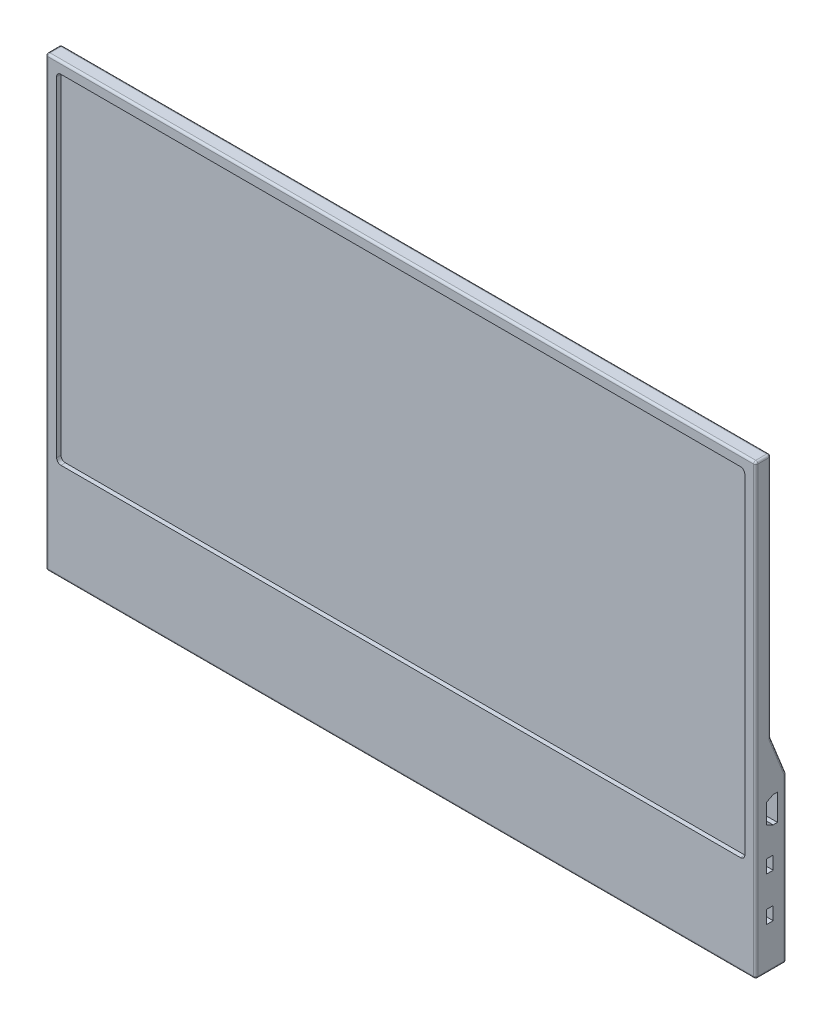
SolidWorks part; units mm, degrees
ref_plane "前视基准面" through (0, 0, 0) normal (0, 0, 1) x (1, 0, 0)
ref_plane "上视基准面" through (0, 0, 0) normal (0, 1, 0) x (1, 0, 0)
ref_plane "右视基准面" through (0, 0, 0) normal (1, 0, 0) x (0, 0, -1)
other "Configuration Table"
ref_plane "基准面1" through (0, 0, 7) normal (0, 0, 1) x (1, 0, 0)
sketch "草图1" plane through (0, 0, 7) normal (0, 0, 1) x (1, 0, 0)
  line L0 (162.5, -102.5) -> (162.5, 102.5)
  line L1 (162.5, 102.5) -> (-162.5, 102.5)
  line L2 (-162.5, 102.5) -> (-162.5, -102.5)
  line L3 (-162.5, -102.5) -> (162.5, -102.5)
  dimension "D1" = 325
  dimension "D2" = 205
extrude "凸台-拉伸1" add sketch "草图1" against normal blind 14
sketch "草图2" plane through (162.5, 0, 0) normal (1, 0, 0) x (0, 0, -1)
  line L0 (7, 102.5) -> (0, 102.5)
  line L1 (0, 102.5) -> (0, -27.5)
  line L2 (0, -27.5) -> (7, -27.5)
  line L3 (7, -27.5) -> (7, 102.5)
  line L4 (-7, -102.5) -> (-7, 102.5) construction
  line L5 (7, -102.5) -> (-7, -102.5) construction
  dimension "D1" = 7
  dimension "D2" = 14
  dimension "D3" = 75
  dimension "D4" = 205
extrude "切除-拉伸1" cut sketch "草图2" against normal through all
sketch "草图3" plane through (162.5, 0, 0) normal (1, 0, 0) x (0, 0, -1)
  line L0 (-2, -43.5) -> (0.9464, -45)
  line L1 (0.9464, -45) -> (2.9464, -45)
  line L2 (2.9464, -45) -> (2.9464, -33)
  line L3 (2.9464, -33) -> (0.9464, -33)
  line L4 (0.9464, -33) -> (-2, -34.5)
  line L5 (-2, -34.5) -> (-2, -43.5)
  line L6 (0, -27.5) -> (7, -27.5) construction
  line L7 (0, 102.5) -> (0, -27.5) construction
  dimension "D1" = 0.9464
  dimension "D2" = 2.9464
  dimension "D3" = 2
  dimension "D4" = 5.5
  dimension "D5" = 7
  dimension "D6" = 16
  dimension "D7" = 17.5
extrude "切除-拉伸2" cut sketch "草图3" against normal blind 10
sketch "草图4" plane through (162.5, 0, 0) normal (1, 0, 0) x (0, 0, -1)
  line L0 (-2, -57) -> (-2, -63)
  line L1 (-2, -63) -> (1, -63)
  line L2 (1, -63) -> (1, -57)
  line L3 (1, -57) -> (-2, -57)
  line L5 (0.9464, -45) -> (2.9464, -45) construction
  line L6 (2.9464, -45) -> (2.9464, -33) construction
  dimension "D1" = 1.9464
  dimension "D2" = 4.9464
  dimension "D3" = 12
  dimension "D4" = 18
extrude "切除-拉伸3" cut sketch "草图4" against normal blind 10
sketch "草图5" plane through (162.5, 0, 0) normal (1, 0, 0) x (0, 0, -1)
  line L0 (-2, -77) -> (-2, -83)
  line L1 (-2, -83) -> (1, -83)
  line L2 (1, -83) -> (1, -77)
  line L3 (1, -77) -> (-2, -77)
  line L4 (1, -63) -> (1, -57) construction
  line L5 (-2, -63) -> (1, -63) construction
  dimension "D1" = 3
  dimension "D2" = 14
  dimension "D3" = 20
extrude "切除-拉伸4" cut sketch "草图5" against normal blind 10
sketch "草图6" plane through (0, 0, 7) normal (0, 0, 1) x (1, 0, 0)
  line L0 (-157.5, -57.5) -> (157.5, -57.5)
  line L1 (157.5, -57.5) -> (157.5, 97.5)
  line L2 (157.5, 97.5) -> (-157.5, 97.5)
  line L3 (-157.5, 97.5) -> (-157.5, -57.5)
  line L4 (162.5, -102.5) -> (162.5, 102.5) construction
  line L5 (-162.5, -102.5) -> (162.5, -102.5) construction
  dimension "D1" = 5
  dimension "D2" = 320
  dimension "D3" = 45
  dimension "D4" = 200
extrude "切除-拉伸5" cut sketch "草图6" against normal blind 2
draft "拔模1" type of draft neutral plane draft angle 68.199 faces to draft 1 face at (0, -27.5, -3.5) neutral plane through (0, 0, -7) neutral plane normal (0, 0, -1) parameters "D1"=68.199
hole_wizard "Ø3.5 (3.5) 直径孔1" positions "草图8" profile "草图7" hole size "Ø3.5" standard "ANSI Metric"
sketch "草图8" plane through (0, 0, -7) normal (0, 0, -1) x (-1, 0, 0)
  point P0 (-37.55, -37.75)
  point P1 (37.55, -37.75)
sketch "草图7" plane through (37.55, -37.75, -7) normal (1, 0, 0) x (0, 1, 0)
  line L0 (0, 0) -> (0, 5)
  line L1 (0, 5) -> (1.75, 5)
  line L2 (1.75, 5) -> (1.75, 0)
  line L5 (1.75, 0) -> (0, 0)
  line L10 (0, 5) -> (-1.75, 5) construction
  line L11 (0, -6.35) -> (0, 107.95) construction
  dimension "孔直径" = 3.5
  dimension "孔深度" = 5
  dimension "导头角度" = 180
fillet "圆角1" radius 1 18 edges at (0, 102.5, 0) (162.5, 102.5, 3.5) (162.5, -18.75, -3.5) (162.5, 46.25, 0) (-162.5, 102.5, 3.5) (0, 102.5, 7) (-162.5, 46.25, 0) (-162.5, -18.75, -3.5) (0, -27.5, -7) (162.5, 0, 7) (162.5, -65, -7) (162.5, -102.5, 0) (-162.5, 0, 7) (-162.5, -65, -7) (0, -102.5, 7) (0, -102.5, -7) (-162.5, -102.5, 0) (0, -10, 0)
fillet "圆角2" radius 2 4 edges at (157.5, -57.5, 6) (157.5, 97.5, 6) (-157.5, -57.5, 6) (-157.5, 97.5, 6)
